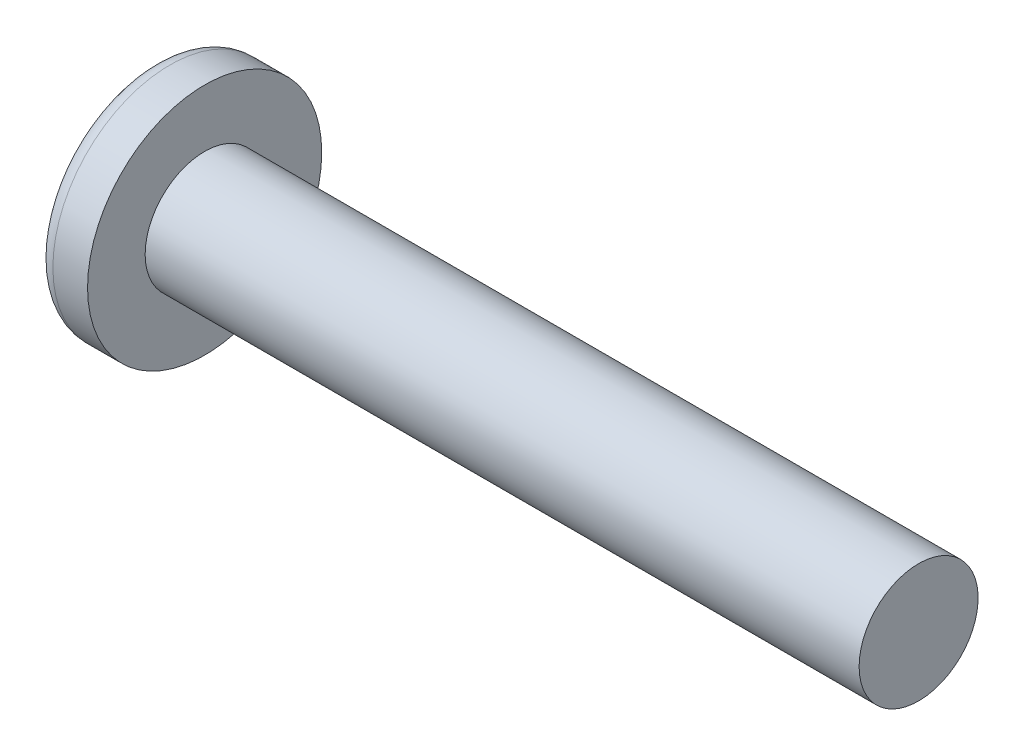
SolidWorks part; units mm, degrees
material "AISI 316 Stainless Steel Sheet (SS)"
ref_plane "Plane1" through (0, 0, 0) normal (0, 0, 1) x (1, 0, 0)
ref_plane "Plane2" through (0, 0, 0) normal (0, 1, 0) x (1, 0, 0)
ref_plane "Plane3" through (0, 0, 0) normal (1, 0, 0) x (0, 0, -1)
sketch "BodySke" plane through (0, 0, 0) normal (0, 0, 1) x (1, 0, 0)
  line L0 (4.445, 3.175) -> (4.445, 6.2484)
  line L1 (4.8984, 6.35) -> (4.8984, -3.175) construction
  line L2 (-25.4, 0) -> (127, 0) construction
  line L3 (42.545, 0) -> (0, 0)
  line L4 (4.445, 3.175) -> (42.545, 3.175)
  line L5 (42.545, 3.175) -> (42.545, 0)
  line L6 (2.5951, 6.2484) -> (4.445, 6.2484)
  line L7 (4.445, -3.175) -> (42.545, -3.175) construction
  line L8 (17.145, 6.35) -> (17.145, -3.175) construction
  arc A0 (1.8697, 5.8733) -> (0, 0) centre (10.16, 0) ccw
  arc A2 (1.8697, 5.8733) -> (2.5951, 6.2484) centre (2.5951, 5.3594) cw
  dimension "Head_crown_rad" = 10.16
  dimension "Head_fillet_rad" = 0.889
  dimension "Diameter" = 6.35
  dimension "Length" = 38.1
  dimension "Head_ht" = 4.445
  dimension "Head_dia" = 12.4968
  dimension "Advance" = 0.9068
  dimension "Thread_nom" = 25.4
revolve "Base-Revolve" add sketch "BodySke" angle 360 about L2
cosmetic thread "ThreadCosmetic" parameters "Thread_length"=25.4, "Thread_minor"=5.268
sketch "Sketch3" plane through (0, 0, 0) normal (1, 0, 0) x (0, 0, -1)
  line L0 (0.7366, -4.0386) -> (-0.7366, -4.0386)
  line L1 (0.7366, -4.0386) -> (0.7366, 4.0386)
  line L2 (-0.7366, 4.0386) -> (0.7366, 4.0386)
  line L3 (-0.7366, 4.0386) -> (-0.7366, -4.0386)
  dimension "Cross_dia" = 8.0772
  dimension "D1" = 4.0386
  dimension "Cross_width" = 1.4732
  dimension "D2" = 0.7366
ref_plane "Plane4" through (4.572, 0, 0) normal (1, 0, 0) x (0, 0, -1)
sketch "Sketch4" plane through (4.572, 0, 0) normal (1, 0, 0) x (0, 0, -1)
  line L0 (0.3683, -0.3683) -> (-0.3683, -0.3683)
  line L1 (0.3683, -0.3683) -> (0.3683, 0.3683)
  line L2 (-0.3683, 0.3683) -> (0.3683, 0.3683)
  line L3 (-0.3683, 0.3683) -> (-0.3683, -0.3683)
  dimension "D2" = 0.7366
  dimension "D1" = 0.7366
  dimension "D3" = 0.3683
  dimension "D4" = 0.3683
loft "Cut-Loft1" cut profiles "Sketch3", "Sketch4"
pattern_circular "CirPattern1" count 2 every 90 about axis through (0, 0, 0) along (1, 0, 0) of "Cut-Loft1"
sketch "ThdSchSke" plane through (0, 0, 0) normal (0, 0, 1) x (1, 0, 0)
  line L0 (17.145, -2.634) -> (16.7662, -3.175)
  line L1 (17.145, -2.634) -> (17.5238, -3.175)
  line L2 (17.5238, -3.175) -> (17.5238, -3.9687)
  line L3 (-3.175, 0) -> (5.1513, 0) construction
  line L5 (17.5238, -3.9687) -> (16.7662, -3.9687)
  line L6 (16.7662, -3.9687) -> (16.7662, -3.175)
  dimension "Diameter" = 6.35
  dimension "SideAngle" = 55
  dimension "VeeAngle" = 70
  dimension "Thread_minor" = 5.268
  dimension "Overcut" = 7.9375
  dimension "Start" = 17.145
revolve "ThreadSchematic" [suppressed] cut sketch "ThdSchSke" angle 360 about L3
pattern_linear "ThdSchPat" [suppressed]
equation "\"D1@Sketch3\" = \"Cross_dia@Sketch3\" / 2"
equation "\"D2@Sketch3\" = \"Cross_width@Sketch3\" / 2"
equation "\"D1@Sketch4\" = \"Cross_width@Sketch3\" *.5"
equation "\"D2@Sketch4\" = \"D1@Sketch4\""
equation "\"D3@Sketch4\" = \"D1@Sketch4\" / 2"
equation "\"D4@Sketch4\" = \"D2@Sketch4\" / 2"
equation "\"Thread_length@ThreadCosmetic\" = ((sgn( (\"Length@BodySke\" - \"Advance@BodySke\" ) - \"Thread_nom@BodySke\" )-1)*( (\"Length@BodySke\" - \"Advance@BodySke\" ) - \"Thread_nom@BodySke\" ))/-2+ \"Thread_nom@BodySke\""
equation "\"Thread_minor@ThdSchSke\" = \"Thread_minor@ThreadCosmetic\""
equation "\"Diameter@ThdSchSke\" = \"Diameter@BodySke\""
equation "\"Overcut@ThdSchSke\" = \"Diameter@BodySke\" * 1.25"
equation "\"Start@ThdSchSke\" = \"Head_ht@BodySke\" + \"Length@BodySke\" - \"Thread_length@ThreadCosmetic\"  '---Non-countersunk---"
equation "\"Num_threads@ThdSchPat\" = int( \"Thread_length@ThreadCosmetic\" / \"Advance@BodySke\" + 0.999 )  + 1"
equation "\"Advance@ThdSchPat\" = \"Thread_length@ThreadCosmetic\" /  (\"Num_threads@ThdSchPat\" - 1) 'relax it"
